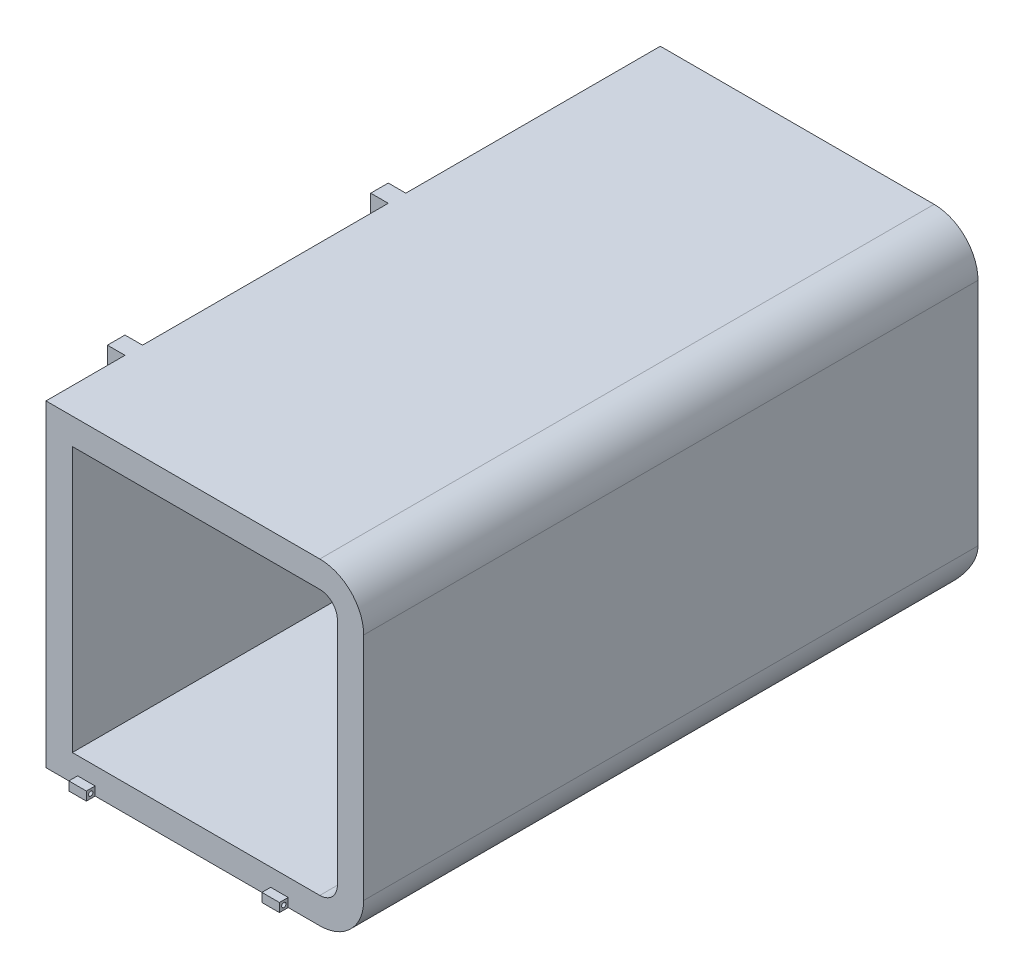
SolidWorks part; units mm, degrees
ref_plane "Front Plane" through (0, 0, 0) normal (0, 0, 1) x (1, 0, 0)
ref_plane "Top Plane" through (0, 0, 0) normal (0, 1, 0) x (1, 0, 0)
ref_plane "Right Plane" through (0, 0, 0) normal (1, 0, 0) x (0, 0, -1)
sketch "Sketch1" plane through (0, 0, 0) normal (0, 0, 1) x (1, 0, 0)
  line L0 (10.3, 6.55) -> (10.3, -6.55)
  line L5 (-7.8, 9.05) -> (7.8, 9.05)
  line L10 (-7.8, 9.05) -> (-7.8, -9.05)
  line L11 (-7.8, -9.05) -> (7.8, -9.05)
  line L13 (-7.8, 0) -> (0, 0) construction
  line L14 (0, 0) -> (0, 9.05) construction
  line L16 (-6.3, 7.55) -> (7.8, 7.55)
  line L17 (8.8, 6.55) -> (8.8, -6.55)
  line L18 (-6.3, -7.55) -> (7.8, -7.55)
  line L19 (-6.3, 7.55) -> (-6.3, -7.55)
  arc A10 (7.8, -9.05) -> (10.3, -6.55) centre (7.8, -6.55) ccw
  arc A11 (7.8, 9.05) -> (10.3, 6.55) centre (7.8, 6.55) cw
  arc A12 (7.8, 7.55) -> (8.8, 6.55) centre (7.8, 6.55) cw
  arc A13 (7.8, -7.55) -> (8.8, -6.55) centre (7.8, -6.55) ccw
  point P11 (10.3, 9.05)
  dimension "D3" = 2.5
  dimension "D2" = 18.1
  dimension "D1" = 18.1
  dimension "D4" = 1.5
extrude "Boss-Extrude1" add sketch "Sketch1" along normal blind 35
sketch "Sketch4" plane through (0, 0, 0) normal (0, 0, -1) x (-1, 0, 0)
  line L4 (7.8, -9.05) -> (7.8, 9.05)
  line L5 (7.8, 9.05) -> (-7.8, 9.05)
  line L6 (-10.3, 6.55) -> (-10.3, -6.55)
  line L7 (-7.8, -9.05) -> (7.8, -9.05)
  line L8 (7.8, -9.05) -> (7.8, 9.05)
  line L9 (7.8, 9.05) -> (-7.8, 9.05)
  line L11 (-7.8, -9.05) -> (7.8, -9.05)
  line L12 (-10.3, 6.55) -> (-10.3, -6.55)
  arc A2 (-7.8, 9.05) -> (-10.3, 6.55) centre (-7.8, 6.55) ccw
  arc A3 (-7.8, 9.05) -> (-10.3, 6.55) centre (-7.8, 6.55) ccw
  arc A6 (-10.3, -6.55) -> (-7.8, -9.05) centre (-7.8, -6.55) ccw
  arc A7 (-10.3, -6.55) -> (-7.8, -9.05) centre (-7.8, -6.55) ccw
  dimension "D1" = 0
extrude "Boss-Extrude3" add sketch "Sketch4" against normal blind 1.5
sketch "Sketch5" plane through (0, -9.05, 0) normal (0, -1, 0) x (1, 0, 0)
  line L0 (-7.8, 0) -> (-7.8, 15) construction
  line L1 (-7.8, 35) -> (-7.8, 0) construction
  line L2 (-8.8, 15) -> (-7.8, 15) construction
  line L3 (-7.8, 15.5) -> (-8.8, 15.5)
  line L4 (-7.8, 15.5) -> (-7.8, 14.5)
  line L5 (-7.8, 14.5) -> (-8.8, 14.5)
  line L6 (-8.8, 15.5) -> (-8.8, 14.5)
  line L7 (-7.8, 15) -> (-7.8, 30) construction
  line L9 (-8.8, 30.5) -> (-7.8, 30.5)
  line L10 (-8.8, 30.5) -> (-8.8, 29.5)
  line L11 (-8.8, 29.5) -> (-7.8, 29.5)
  line L12 (-7.8, 30.5) -> (-7.8, 29.5)
  dimension "D1" = 15
  dimension "D2" = 1
  dimension "D3" = 1
  dimension "D4" = 15
  dimension "D5" = 1
  dimension "D6" = 1
extrude "Boss-Extrude4" add sketch "Sketch5" against normal up to surface (18.1 mm away) up to face at (0, 9.05, 17.5)
sketch "Sketch8" plane through (-7.8, 0, 0) normal (-1, 0, 0) x (0, 0, 1)
  line L0 (0, -6.55) -> (0, -9.05)
  line L1 (0, 9.05) -> (0, -9.05) construction
  line L2 (0, -9.05) -> (2.5, -9.05)
  line L3 (14.5, -9.05) -> (0, -9.05) construction
  arc A0 (2.5, -9.05) -> (0, -6.55) centre (2.5, -6.55) cw
  dimension "D1" = 2.5
extrude "Cut-Extrude2" cut sketch "Sketch8" against normal up to surface (18.1 mm away)
sketch "Sketch9" plane through (0, 0, 35) normal (0, 0, 1) x (1, 0, 0)
  line L0 (0, -9.05) -> (0, 0) construction
  line L1 (-7.8, -9.05) -> (7.8, -9.05) construction
  line L2 (-5, -8.55) -> (5, -8.55) construction
  line L3 (-6, -9.05) -> (-5, -9.05)
  line L4 (-6, -9.05) -> (-6, -8.55)
  line L5 (-6, -8.55) -> (-5, -8.55)
  line L6 (-5, -9.05) -> (-5, -8.55)
  line L7 (5, -9.05) -> (6, -9.05)
  line L8 (5, -9.05) -> (5, -8.55)
  line L9 (5, -8.55) -> (6, -8.55)
  line L10 (6, -9.05) -> (6, -8.55)
  point P14 (0, -8.55)
  dimension "D1" = 1
  dimension "D2" = 0.5
  dimension "D3" = 1
  dimension "D4" = 10
extrude "Boss-Extrude5" add sketch "Sketch9" along normal blind 0.5
sketch "Sketch10" plane through (6, 0, 0) normal (1, 0, 0) x (0, 0, -1)
  line L0 (-35.5, -8.8) -> (-35.25, -8.8) construction
  line L1 (-35.5, -9.05) -> (-35.5, -8.55) construction
  line L2 (-35.25, -8.8) -> (-35.25, -8.55) construction
  line L3 (-35.5, -8.55) -> (-35, -8.55) construction
  circle A0 centre (-35.25, -8.8) radius 0.125
  dimension "D1" = 0.25
extrude "Cut-Extrude3" cut sketch "Sketch10" against normal up to surface (12 mm away) up to face at (-6, -8.8, 35.25)
sketch "Sketch11" plane through (0, 0, 1.5) normal (0, 0, 1) x (1, 0, 0)
  circle A0 centre (0, 0) radius 2.5
  dimension "D1" = 5
extrude "Boss-Extrude6" add sketch "Sketch11" along normal blind 1.5
sketch "Sketch23" plane through (-7.8, 0, 0) normal (-1, 0, 0) x (0, 0, 1)
  line L0 (6.4735, -9.05) -> (6.4735, -4.9474) construction
  line L1 (14.5, -9.05) -> (2.5, -9.05) construction
  line L2 (6.4735, -4.9474) -> (0, -4.9474) construction
  line L3 (0, 9.05) -> (0, -6.55) construction
  circle A2 centre (6.4735, -4.9474) radius 0.5
  dimension "D3" = 1
  dimension "D1" = 6.4735
  dimension "D2" = 4.1026
extrude "Cut-Extrude12" cut sketch "Sketch23" against normal up to surface (1.5 mm away) up to face at (-6.3, 0, 18.25)
sketch "Sketch26" plane through (-6.3, 0, 0) normal (1, 0, 0) x (0, 0, -1)
  line L0 (-2, -7.05) -> (-7.7499, -7.05)
  line L1 (-1.5, -7.55) -> (-8.2499, -7.55)
  line L2 (-1.5, -7.55) -> (-1.5, 1.0484)
  line L3 (-1.5, 1.0484) -> (-8.2499, 1.0484)
  line L4 (-8.2499, -7.55) -> (-8.2499, 1.0484)
  line L5 (-7.7499, -7.05) -> (-7.7499, 0.5484)
  line L6 (-2, 0.5484) -> (-7.7499, 0.5484)
  line L7 (-2, -7.05) -> (-2, 0.5484)
  dimension "D1" = 0.5
extrude "Boss-Extrude16" add sketch "Sketch26" along normal blind 2.05
sketch "Sketch27" plane through (-4.25, 0, 0) normal (1, 0, 0) x (0, 0, -1)
  line L1 (-1.957, 0.573) -> (-2.5514, 0.573)
  line L2 (-1.957, 0.573) -> (-1.957, 0.1154)
  line L3 (-1.957, 0.1154) -> (-2.5514, 0.1154)
  line L4 (-2.5514, 0.573) -> (-2.5514, 0.1154)
  circle A0 centre (-2.2391, 0.3172) radius 0.1541
extrude "Boss-Extrude23" add sketch "Sketch27" along normal up to surface (1.8165 mm away)
sketch "Sketch28" plane through (-4.25, 0, 0) normal (1, 0, 0) x (0, 0, -1)
  line L4 (-1.5, -7.55) -> (-1.5, 1.0484)
  line L5 (-1.5, 1.0484) -> (-8.2499, 1.0484)
  line L6 (-8.2499, 1.0484) -> (-8.2499, -7.55)
  line L7 (-8.2499, -7.55) -> (-1.5, -7.55)
  line L8 (-1.5, -7.55) -> (-1.5, 1.0484)
  line L9 (-1.5, 1.0484) -> (-8.2499, 1.0484)
  line L10 (-8.2499, 1.0484) -> (-8.2499, -7.55)
  line L11 (-8.2499, -7.55) -> (-1.5, -7.55)
  dimension "D1" = 0
extrude "Boss-Extrude24" add sketch "Sketch28" along normal blind 0.5
sketch "Sketch29" plane through (-4.25, 0, 0) normal (-1, 0, 0) x (0, 0, 1)
  circle A0 centre (2.2391, 0.3172) radius 0.1541 construction
  circle A1 centre (2.2391, 0.3172) radius 0.1541
extrude "Cut-Extrude13" cut sketch "Sketch29" against normal blind 2.5
sketch "Sketch30" plane through (0, 0, 3) normal (0, 0, 1) x (1, 0, 0)
  circle A0 centre (0, 0) radius 1.7357
extrude "Cut-Extrude14" cut sketch "Sketch30" against normal blind 0.5
